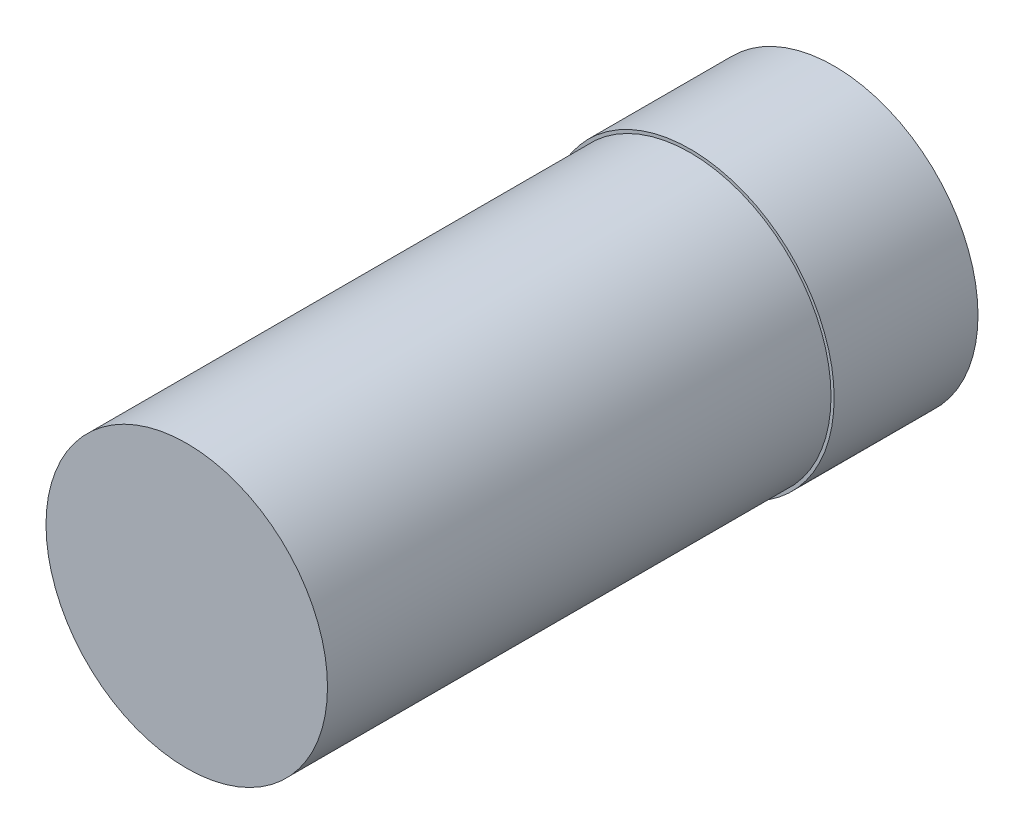
SolidWorks part; units mm, degrees
ref_plane "정면" through (0, 0, 0) normal (0, 0, 1) x (1, 0, 0)
ref_plane "윗면" through (0, 0, 0) normal (0, 1, 0) x (1, 0, 0)
ref_plane "우측면" through (0, 0, 0) normal (1, 0, 0) x (0, 0, -1)
sketch "스케치1" plane through (0, 0, 0) normal (0, 0, 1) x (1, 0, 0)
  circle A0 centre (0, 0) radius 3
  dimension "D1" = 6
extrude "보스-돌출1" add sketch "스케치1" along normal blind 3
sketch "스케치2" plane through (0, 0, 3) normal (0, 0, 1) x (1, 0, 0)
  circle A0 centre (0, 0) radius 2.935
  dimension "D1" = 5.87
extrude "보스-돌출2" add sketch "스케치2" along normal blind 10.5
sketch "스케치3" plane through (0, 0, 13.5) normal (0, 0, 1) x (1, 0, 0)
  circle A0 centre (0, 0) radius 2.45
  dimension "D1" = 4.9
